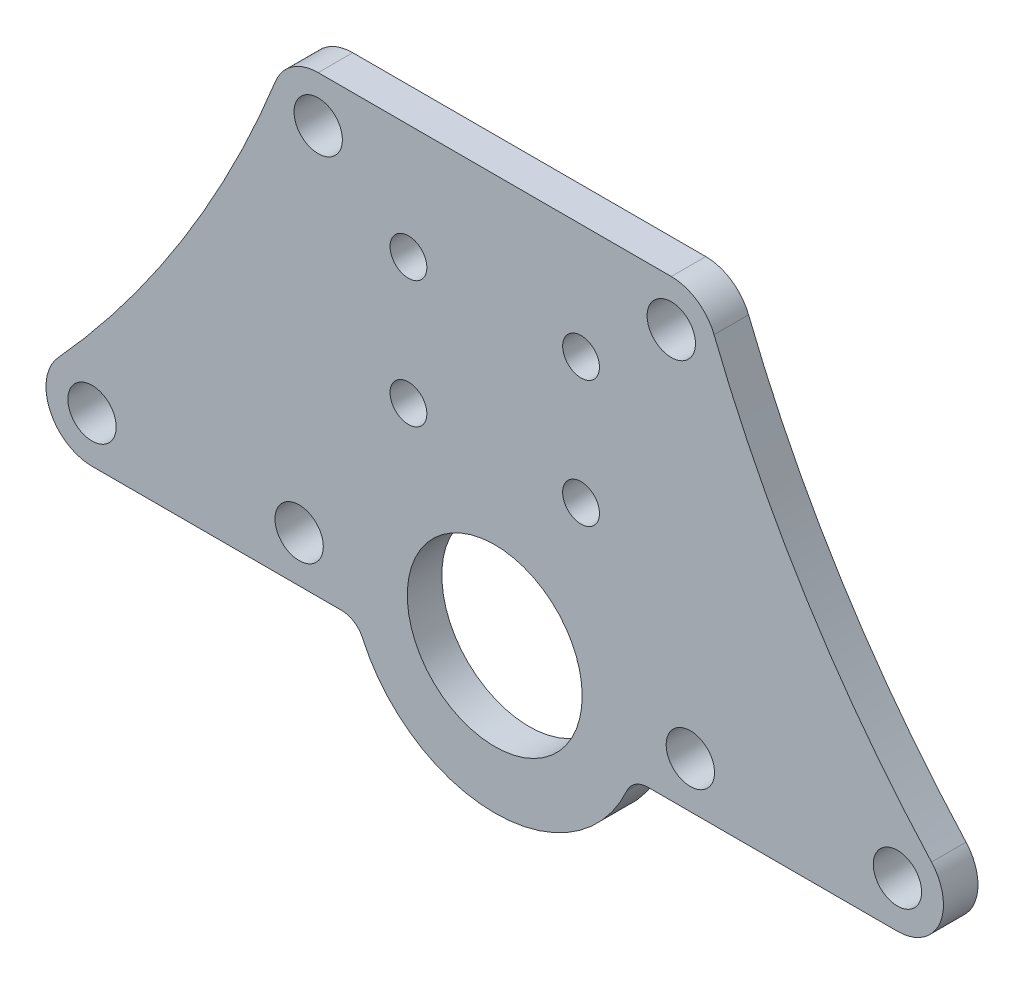
SolidWorks part; units mm, degrees
material "5052-H34"
ref_plane "正面" through (0, 0, 0) normal (0, 0, 1) x (1, 0, 0)
ref_plane "平面" through (0, 0, 0) normal (0, 1, 0) x (1, 0, 0)
ref_plane "右側面" through (0, 0, 0) normal (1, 0, 0) x (0, 0, -1)
sketch "ｽｹｯﾁ1" plane through (0, 0, 0) normal (0, 0, 1) x (1, 0, 0)
  line L0 (0, 5.5) -> (0, 0) construction
  line L1 (-7.5, 5.5) -> (7.5, 5.5) construction
  line L2 (-7.5, 5.5) -> (-7.5, -5.5) construction
  line L3 (-7.5, -5.5) -> (7.5, -5.5) construction
  line L4 (7.5, 5.5) -> (7.5, -5.5) construction
  line L5 (-7.5, 5.5) -> (7.5, -5.5) construction
  line L6 (-7.5, -5.5) -> (7.5, 5.5) construction
  line L7 (0, 0) -> (7.5, 0) construction
  line L8 (0, 0) -> (0, -20) construction
  line L9 (0, -12.5) -> (0, 29.8609) construction
  line L10 (0, -20) -> (35, -20) construction
  line L11 (0, -20) -> (15.343, 11.4578) construction
  line L12 (0, -20) -> (111.9546, 49.957) construction
  line L13 (-35, -24) -> (0, -24)
  line L14 (-15.343, 15.4578) -> (15.343, 15.4578)
  line L15 (0, -24) -> (35, -24)
  circle A0 centre (7.5, 5.5) radius 1.6
  circle A1 centre (-7.5, 5.5) radius 1.6
  circle A2 centre (7.5, -5.5) radius 1.6
  circle A3 centre (-7.5, -5.5) radius 1.6
  circle A4 centre (0, -20) radius 7.6
  circle A5 centre (0, -20) radius 30 construction
  arc A6 (0, 15) -> (5.9222, 14.4953) centre (0, -20) ccw construction
  circle A7 centre (35, -20) radius 2.1
  circle A8 centre (-35, -20) radius 2.1
  circle A9 centre (15.343, 11.4578) radius 2.1
  circle A10 centre (-15.343, 11.4578) radius 2.1
  arc A11 (34.7714, -23.9935) -> (37.9598, -17.3093) centre (35, -20) ccw
  arc A12 (19.0588, 12.9385) -> (14.7529, 15.414) centre (15.343, 11.4578) ccw
  arc A13 (-34.7714, -23.9935) -> (-37.9598, -17.3093) centre (-35, -20) cw
  arc A14 (-19.0588, 12.9385) -> (-14.7529, 15.414) centre (-15.343, 11.4578) cw
  arc A15 (19.0588, 12.9385) -> (37.9598, -17.3093) centre (111.9546, 49.957) ccw
  circle A16 centre (17, -20) radius 2.1
  arc A17 (-19.0588, 12.9385) -> (-37.9598, -17.3093) centre (-111.9546, 49.957) cw
  arc A18 (5.9222, 14.4953) -> (14.7529, 15.414) centre (0, 114.3198) ccw construction
  arc A19 (0, 214.3198) -> (-14.7529, 15.414) centre (0, 114.3198) ccw construction
  arc A20 (60.5335, 193.9169) -> (0, 214.3198) centre (0, 114.3198) ccw construction
  arc A21 (14.7529, 15.414) -> (-14.7529, 15.414) centre (0, 114.3198) ccw construction
  arc A22 (-14.7529, 15.414) -> (60.5335, 193.9169) centre (0, 114.3198) ccw construction
  circle A24 centre (0, -20) radius 12.6
  circle A27 centre (-17, -20) radius 2.1
  arc A30 (-14.7529, 15.414) -> (-5.9222, 14.4953) centre (0, 114.3198) ccw construction
  arc A31 (-5.9222, 14.4953) -> (0, 14.3198) centre (0, 114.3198) ccw construction
  arc A32 (0, 14.3198) -> (5.9222, 14.4953) centre (0, 114.3198) ccw construction
  arc A33 (5.9222, 14.4953) -> (0, 15) centre (0, -20) ccw construction
  arc A37 (-11.6535, 13.003) -> (-18.8321, 9.5017) centre (-15.343, 11.4578) cw construction
  arc A38 (-18.8321, 9.5017) -> (-19.0588, 12.9385) centre (-15.343, 11.4578) cw construction
  arc A39 (-14.7529, 15.414) -> (-11.6535, 13.003) centre (-15.343, 11.4578) cw construction
  arc A40 (13.5895, 7.8626) -> (18.8321, 9.5017) centre (15.343, 11.4578) ccw construction
  arc A41 (18.8321, 9.5017) -> (19.0588, 12.9385) centre (15.343, 11.4578) ccw construction
  arc A42 (11.6535, 13.003) -> (13.5895, 7.8626) centre (15.343, 11.4578) ccw construction
  arc A43 (14.7529, 15.414) -> (11.6535, 13.003) centre (15.343, 11.4578) ccw construction
  arc A44 (34.7714, -16.0065) -> (31, -20) centre (35, -20) ccw construction
  arc A45 (31, -20) -> (34.7714, -23.9935) centre (35, -20) ccw construction
  arc A46 (37.9598, -17.3093) -> (34.7714, -16.0065) centre (35, -20) ccw construction
  arc A47 (-34.7714, -16.0065) -> (-34.7714, -23.9935) centre (-35, -20) cw construction
  arc A48 (-37.9598, -17.3093) -> (-34.7714, -16.0065) centre (-35, -20) cw construction
  point P0 (0, 0)
  dimension "D3" = 3.2
  dimension "D4" = 15.2
  dimension "D6" = 60
  dimension "D7" = 70
  dimension "D8" = 4.2
  dimension "D10" = 8
  dimension "D12" = 18
  dimension "D13" = 100
  dimension "D14" = 25.2
  dimension "D11" = 100
  dimension "D1" = 15
  dimension "D2" = 11
  dimension "D5" = 20
  dimension "D9" = 64
extrude "ﾎﾞｽ - 押し出し1" add sketch "ｽｹｯﾁ1" along normal blind 3
fillet "ﾌｨﾚｯﾄ2" radius 2 2 edges at (11.9482, -24, 1.5) (-11.9482, -24, 1.5)
